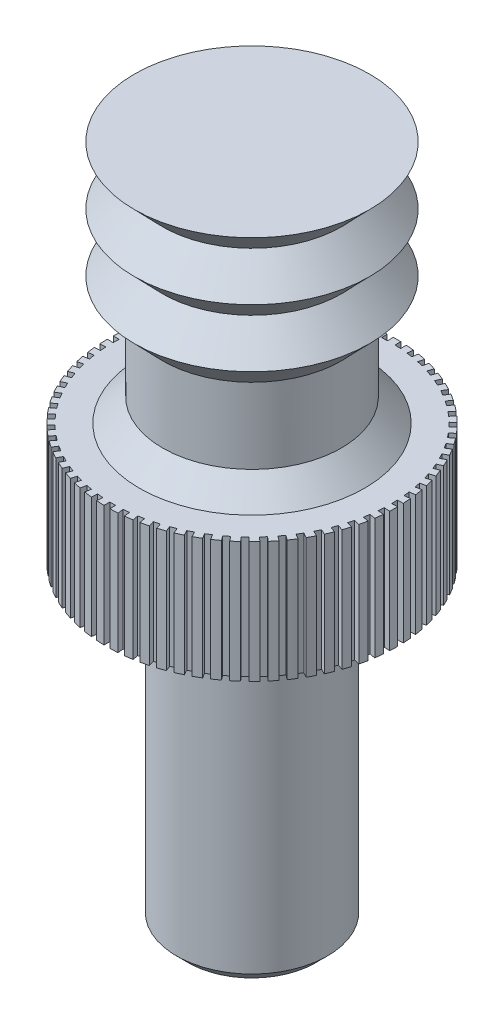
SolidWorks part; units mm, degrees
ref_plane "Front Plane" through (0, 0, 0) normal (0, 0, 1) x (1, 0, 0)
ref_plane "Top Plane" through (0, 0, 0) normal (0, 1, 0) x (1, 0, 0)
ref_plane "Right Plane" through (0, 0, 0) normal (1, 0, 0) x (0, 0, -1)
sketch "Sketch1" plane through (0, 0, 0) normal (0, 0, 1) x (1, 0, 0)
  line L0 (0, 0) -> (0, 65.7285) construction
  line L1 (0, 0) -> (3, 0)
  line L2 (3, 0) -> (3, 1)
  line L3 (3, 1) -> (2.5, 1)
  line L4 (2.5, 1) -> (2.5, 1.5)
  line L5 (2.5, 1.5) -> (6.5, 1.5)
  line L6 (6.5, 1.5) -> (6.5, 28.58)
  line L7 (12.5, 28.58) -> (12.5, 39)
  line L8 (6.5, 28.58) -> (12.5, 28.58)
  line L9 (12.5, 39) -> (7.7, 39)
  line L10 (7.7, 39) -> (7.7, 47.5)
  line L11 (7.7, 47.5) -> (10.125, 50)
  line L12 (10.125, 50) -> (7.7, 52.5)
  line L13 (7.7, 52.5) -> (10.125, 55)
  line L14 (10.125, 55) -> (7.7, 57.5)
  line L15 (7.7, 57.5) -> (10.125, 60)
  line L16 (10.125, 60) -> (0, 60)
  line L17 (0, 60) -> (0, 0)
  line L18 (7.7, 47.5) -> (7.7, 50.754) construction
  line L19 (10.125, 50) -> (10.125, 46.4897) construction
  point P3 (10.1, 39)
  dimension "D1" = 13
  dimension "D2" = 6
  dimension "D3" = 1
  dimension "D4" = 0.5
  dimension "D5" = 10.42
  dimension "D6" = 39
  dimension "D7" = 8.5
  dimension "D8" = 20.25
  dimension "D9" = 25
  dimension "D10" = 15.4
  dimension "D11" = 21
  dimension "D12" = 2.5
revolve "Revolve1" add sketch "Sketch1" angle 360 about L0
sketch "Sketch2" plane through (0, 0, 0) normal (0, -1, 0) x (1, 0, 0)
  circle A0 centre (0, 0) radius 2
  dimension "D1" = 4
extrude "Cut-Extrude1" cut sketch "Sketch2" against normal blind 10
chamfer "Chamfer1" distance 2 angle 45 1 edges at (0, 39, -7.7)
sketch "Sketch3" plane through (0, 28.58, 0) normal (0, -1, 0) x (1, 0, 0)
  line L0 (0, 0) -> (0, 12) construction
  line L2 (-0.25, 12) -> (0.25, 12)
  line L3 (-0.25, 12) -> (-0.25, 15.6902)
  line L4 (-0.25, 15.6902) -> (0.25, 15.6902)
  line L5 (0.25, 12) -> (0.25, 15.6902)
  dimension "D1" = 0.5
  dimension "D2" = 12
extrude "Cut-Extrude2" cut sketch "Sketch3" against normal through all
pattern_circular "CirPattern1" count 67 over 360 about axis through (0, 0, 0) along (0, 1, 0) of "Cut-Extrude2"
chamfer "Chamfer2" distance 1 angle 45 1 edges at (0, 1.5, -6.5)
